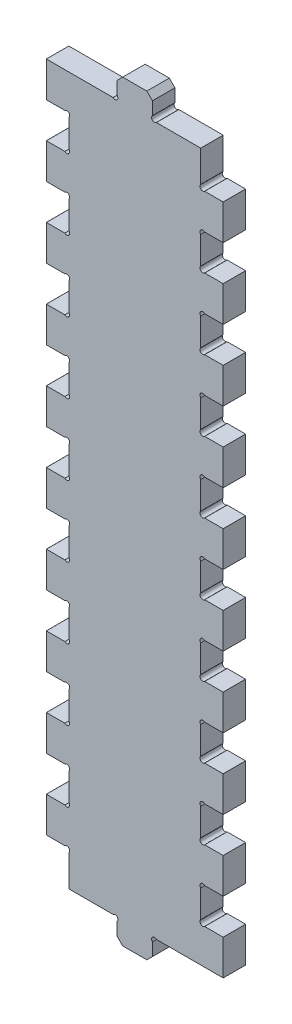
SolidWorks part; units mm, degrees
material "PVC Rigid"
ref_plane "Front Plane" through (0, 0, 0) normal (0, 0, 1) x (1, 0, 0)
ref_plane "Top Plane" through (0, 0, 0) normal (0, 1, 0) x (1, 0, 0)
ref_plane "Right Plane" through (0, 0, 0) normal (1, 0, 0) x (0, 0, -1)
sketch "Model" [suppressed]
  dimension "D3" = 0.7937
  dimension "D1" = 10
  dimension "D2" = 10
sketch "Sketch1" plane through (0, 0, 0) normal (0, 0, 1) x (1, 0, 0)
  line L1 (0, 0) -> (50, 0)
  line L2 (0, 0) -> (0, 200.0001)
  line L3 (0, 200.0001) -> (50, 200.0001)
  line L4 (50, 0) -> (50, 200.0001)
  dimension "D1" = 200.0001
  dimension "D2" = 50
extrude "Boss-Extrude1" add sketch "Sketch1" along normal blind 6.35
sketch "Sketch2" plane through (0, 0, 0) normal (0, 0, 1) x (1, 0, 0)
  line L0 (0, 100.0001) -> (50, 100.0001) construction
  line L1 (50, 200.0001) -> (0, 200.0001) construction
  line L2 (25, 200.0001) -> (25, 203.1751) construction
  line L3 (20, 206.3501) -> (30, 206.3501)
  line L4 (20, 206.3501) -> (20, 200.0001)
  line L5 (20, 200.0001) -> (30, 200.0001)
  line L6 (30, 206.3501) -> (30, 200.0001)
  line L7 (20, 206.3501) -> (30, 200.0001) construction
  line L8 (20, 200.0001) -> (30, 206.3501) construction
  line L9 (0, 200.0001) -> (0, 0) construction
  line L10 (50, 0) -> (50, 200.0001) construction
  line L11 (20, 0) -> (30, -6.35) construction
  line L12 (20, -6.35) -> (30, 0) construction
  line L13 (25, 0) -> (25, -3.175) construction
  line L14 (30, -6.35) -> (30, 0)
  line L15 (20, 0) -> (30, 0)
  line L16 (20, -6.35) -> (20, 0)
  line L17 (20, -6.35) -> (30, -6.35)
  dimension "D1" = 6.35
  dimension "D2" = 10
extrude "Boss-Extrude2" add sketch "Sketch2" along normal blind 6.35
sketch "Sketch3" plane through (0, 0, 6.35) normal (0, 0, 1) x (1, 0, 0)
  line L0 (25, 206.3501) -> (25, -6.35) construction
  line L1 (30, 206.3501) -> (20, 206.3501) construction
  line L2 (20, -6.35) -> (30, -6.35) construction
  line L3 (6.35, 200.0001) -> (6.35, 0) construction
  line L4 (20, 200.0001) -> (0, 200.0001) construction
  line L5 (0, 0) -> (20, 0) construction
  line L6 (0, 200.0001) -> (0, 0) construction
  line L7 (6.35, 0) -> (0, 0)
  line L8 (6.35, 0) -> (6.35, 10)
  line L9 (6.35, 10) -> (0, 10)
  line L10 (0, 0) -> (0, 10)
  line L11 (50, 0) -> (50, 10)
  line L12 (43.65, 10) -> (50, 10)
  line L13 (43.65, 0) -> (43.65, 10)
  line L14 (43.65, 0) -> (50, 0)
  dimension "D1" = 6.35
  dimension "D2" = 10
extrude "Cut-Extrude1" [suppressed] cut sketch "Sketch3" against normal blind 6.35
pattern_linear "LPattern2" [suppressed] count 10 spacing 20
sketch "Sketch4" [suppressed] plane through (0, 0, 6.35) normal (0, 0, 1) x (1, 0, 0)
  line L0 (0, 10) -> (6.35, 0) construction
  line L1 (6.35, 10) -> (5.2275, 10) construction
  line L2 (0.5613, 0.5613) -> (5.7887, 0.5613) construction
  line L3 (0.5613, 0.5613) -> (0.5613, 9.4387) construction
  line L4 (0.5613, 9.4387) -> (5.7887, 9.4387) construction
  line L5 (5.7887, 0.5613) -> (5.7887, 9.4387) construction
  line L6 (0.5613, 0.5613) -> (5.7887, 9.4387) construction
  line L7 (0.5613, 9.4387) -> (5.7887, 0.5613) construction
  line L8 (6.35, 10) -> (0, 10) construction
  line L9 (6.35, 10) -> (6.35, 8.8775) construction
  line L10 (6.35, 0) -> (6.35, 10) construction
  line L11 (25, 206.3501) -> (25, -6.35) construction
  line L12 (30, 206.3501) -> (20, 206.3501) construction
  line L13 (20, -6.35) -> (30, -6.35) construction
  line L14 (44.2113, 9.4387) -> (44.2113, 20.5613) construction
  line L15 (43.65, 10) -> (43.65, 8.8775) construction
  line L16 (49.4387, 9.4387) -> (44.2113, 0.5613) construction
  line L17 (49.4387, 0.5613) -> (44.2113, 9.4387) construction
  line L18 (44.2113, 0.5613) -> (44.2113, 9.4387) construction
  line L19 (49.4387, 9.4387) -> (44.2113, 9.4387) construction
  line L20 (49.4387, 0.5613) -> (49.4387, 9.4387) construction
  line L21 (49.4387, 0.5613) -> (44.2113, 0.5613) construction
  line L22 (43.65, 10) -> (44.7725, 10) construction
  line L23 (5.7887, 9.4387) -> (5.7887, 20.5613) construction
  line L24 (50, 10) -> (43.65, 0) construction
  circle A0 centre (5.7887, 9.4387) radius 0.7938
  circle A4 centre (5.7887, 20.5613) radius 0.7938
  circle A7 centre (44.2113, 20.5613) radius 0.7937
  circle A8 centre (44.2113, 9.4387) radius 0.7937
  point P4 (3.175, 5)
  point P40 (46.825, 5)
  dimension "D1" = 1.5875
extrude "Cut-Extrude3" [suppressed] cut sketch "Sketch4" against normal blind 6.35
pattern_linear "LPattern3" [suppressed] count 9 spacing 20
sketch "Sketch8" plane through (0, 0, 6.35) normal (0, 0, 1) x (1, 0, 0)
  line L0 (6.35, 200.0001) -> (6.35, 0) construction
  line L1 (20, 200.0001) -> (0, 200.0001) construction
  line L2 (0, 0) -> (20, 0) construction
  line L3 (0, 200.0001) -> (0, 0) construction
  line L4 (43.65, 200.0001) -> (43.65, 0) construction
  line L5 (0, 0) -> (6.35, 0)
  line L6 (0, 0) -> (0, 10)
  line L7 (0, 10) -> (6.35, 10)
  line L8 (6.35, 0) -> (6.35, 10)
  line L9 (50, 200.0001) -> (30, 200.0001) construction
  line L10 (30, 0) -> (50, 0) construction
  line L11 (50, 0) -> (50, 200.0001) construction
  line L12 (43.65, 10) -> (50, 10)
  line L13 (43.65, 10) -> (43.65, 20)
  line L14 (43.65, 20) -> (50, 20)
  line L15 (50, 10) -> (50, 20)
  dimension "D1" = 6.35
  dimension "D2" = 10
  dimension "D3" = 10
  dimension "D4" = 6.35
  dimension "D5" = 10
extrude "Cut-Extrude6" cut sketch "Sketch8" against normal through all
pattern_linear "LPattern4" count 10 spacing 20 along (0, 1, 0) of "Cut-Extrude6"
sketch "Sketch9" plane through (0, 0, 6.35) normal (0, 0, 1) x (1, 0, 0)
  line L0 (0, 30) -> (6.35, 20) construction
  line L1 (6.35, 30) -> (5.2275, 30) construction
  line L2 (0.5613, 20.5613) -> (5.7887, 20.5613) construction
  line L3 (0.5613, 20.5613) -> (0.5613, 29.4388) construction
  line L4 (0.5613, 29.4388) -> (5.7887, 29.4388) construction
  line L5 (5.7887, 20.5613) -> (5.7887, 29.4388) construction
  line L6 (0.5613, 20.5613) -> (5.7887, 29.4388) construction
  line L7 (0.5613, 29.4388) -> (5.7887, 20.5613) construction
  line L8 (6.35, 30) -> (0, 30) construction
  line L9 (6.35, 30) -> (6.35, 28.8775) construction
  line L10 (6.35, 20) -> (6.35, 30) construction
  line L11 (43.65, 20) -> (50, 10) construction
  line L12 (43.65, 20) -> (44.7725, 20) construction
  line L13 (44.2113, 10.5613) -> (49.4387, 10.5613) construction
  line L14 (44.2113, 10.5613) -> (44.2113, 19.4387) construction
  line L15 (44.2113, 19.4387) -> (49.4387, 19.4387) construction
  line L16 (49.4387, 10.5613) -> (49.4387, 19.4387) construction
  line L17 (44.2113, 10.5613) -> (49.4387, 19.4387) construction
  line L18 (44.2113, 19.4387) -> (49.4387, 10.5613) construction
  line L19 (50, 20) -> (43.65, 20) construction
  line L20 (43.65, 20) -> (43.65, 18.8775) construction
  line L21 (43.65, 20) -> (43.65, 10) construction
  line L22 (50, 20) -> (50, 30) construction
  circle A0 centre (5.7887, 29.4388) radius 0.7938
  circle A1 centre (5.7887, 20.5613) radius 0.7938
  circle A2 centre (44.2113, 19.4387) radius 0.7937
  circle A3 centre (44.2113, 10.5613) radius 0.7937
  point P4 (3.175, 25)
  point P23 (46.825, 15)
  dimension "D1" = 1.5875
  dimension "D2" = 10
extrude "Cut-Extrude7" cut sketch "Sketch9" against normal through all
pattern_linear "LPattern5" count 9 spacing 20 along (0, 1, 0) of "Cut-Extrude7"
sketch "Sketch10" plane through (0, 0, 6.35) normal (0, 0, 1) x (1, 0, 0)
  line L0 (0, 10) -> (6.35, 0) construction
  line L1 (5.2275, 10) -> (6.35, 10) construction
  line L2 (0.5613, 0.5613) -> (5.7887, 0.5613) construction
  line L3 (0.5613, 0.5613) -> (0.5613, 9.4387) construction
  line L4 (0.5613, 9.4387) -> (5.7887, 9.4387) construction
  line L5 (5.7887, 0.5613) -> (5.7887, 9.4387) construction
  line L6 (0.5613, 0.5613) -> (5.7887, 9.4387) construction
  line L7 (0.5613, 9.4387) -> (5.7887, 0.5613) construction
  line L8 (6.35, 10) -> (0, 10) construction
  line L9 (6.35, 10) -> (6.35, 8.8775) construction
  line L10 (6.35, 0) -> (6.35, 10) construction
  line L11 (6.35, 5) -> (3.175, 5) construction
  line L12 (0, 200.0001) -> (50, 0) construction
  line L13 (43.65, 200.0001) -> (50, 190.0001) construction
  line L14 (44.7725, 190.0001) -> (43.65, 190.0001) construction
  line L15 (44.2113, 190.5614) -> (49.4387, 190.5614) construction
  line L16 (44.2113, 190.5614) -> (44.2113, 199.4388) construction
  line L17 (44.2113, 199.4388) -> (49.4387, 199.4388) construction
  line L18 (49.4387, 190.5614) -> (49.4387, 199.4388) construction
  line L19 (44.2113, 190.5614) -> (49.4387, 199.4388) construction
  line L20 (44.2113, 199.4388) -> (49.4387, 190.5614) construction
  line L21 (43.65, 190.0001) -> (50, 190.0001) construction
  line L22 (43.65, 190.0001) -> (43.65, 191.1226) construction
  line L23 (43.65, 200.0001) -> (43.65, 190.0001) construction
  circle A0 centre (5.7887, 9.4387) radius 0.7938
  circle A2 centre (44.2113, 190.5614) radius 0.7937
  point P4 (3.175, 5)
  point P28 (46.825, 195.0001)
  dimension "D1" = 1.5875
  dimension "D2" = 1.5875
extrude "Cut-Extrude8" cut sketch "Sketch10" against normal through all
chamfer "Chamfer1" distance 1.5875 angle 45 4 edges at (30, -6.35, 3.175) (20, -6.35, 3.175) (20, 206.3501, 3.175) (30, 206.3501, 3.175)
sketch "Sketch5" [suppressed] plane through (0, 0, 6.35) normal (0, 0, 1) x (1, 0, 0)
  line L0 (6.35, 180.0001) -> (0, 190.0001) construction
  line L1 (6.35, 190.0001) -> (5.2275, 190.0001) construction
  line L2 (0.5613, 180.5614) -> (5.7887, 180.5614) construction
  line L3 (0.5613, 180.5614) -> (0.5613, 189.4388) construction
  line L4 (0.5613, 189.4388) -> (5.7887, 189.4388) construction
  line L5 (5.7887, 180.5614) -> (5.7887, 189.4388) construction
  line L6 (0.5613, 180.5614) -> (5.7887, 189.4388) construction
  line L7 (0.5613, 189.4388) -> (5.7887, 180.5614) construction
  line L8 (6.35, 190.0001) -> (0, 190.0001) construction
  line L9 (6.35, 190.0001) -> (6.35, 188.8776) construction
  line L10 (6.35, 181.1226) -> (6.35, 190.0001) construction
  line L15 (25, 206.3501) -> (25, -6.35) construction
  line L16 (28.4125, 206.3501) -> (21.5875, 206.3501) construction
  line L17 (21.5875, -6.35) -> (28.4125, -6.35) construction
  line L20 (43.65, 190.0001) -> (43.65, 188.8776) construction
  line L21 (49.4387, 189.4388) -> (44.2113, 180.5614) construction
  line L22 (49.4387, 180.5614) -> (44.2113, 189.4388) construction
  line L23 (44.2113, 180.5614) -> (44.2113, 189.4388) construction
  line L24 (49.4387, 189.4388) -> (44.2113, 189.4388) construction
  line L25 (49.4387, 180.5614) -> (49.4387, 189.4388) construction
  line L26 (49.4387, 180.5614) -> (44.2113, 180.5614) construction
  line L27 (43.65, 190.0001) -> (44.7725, 190.0001) construction
  line L28 (43.65, 180.0001) -> (50, 190.0001) construction
  line L29 (50, 100.0001) -> (0, 100.0001) construction
  arc A0 (5.2275, 180.0001) -> (6.35, 181.1226) centre (5.7887, 180.5614) ccw construction
  circle A1 centre (5.7887, 189.4388) radius 0.7938
  circle A4 centre (44.2113, 189.4388) radius 0.7937
  point P6 (3.175, 185.0001)
  point P51 (46.825, 185.0001)
  point P56 (25, 100.0001)
  dimension "D1" = 1.5875
extrude "Cut-Extrude4" [suppressed] cut sketch "Sketch5" against normal blind 6.35
sketch "Sketch11" plane through (0, 0, 0) normal (0, 0, 1) x (1, 0, 0)
  line L0 (28.4125, 206.3501) -> (21.5875, 206.3501) construction
  line L11 (20, 201.1226) -> (20, 200.0001) construction
  line L13 (20, 200.0001) -> (18.8775, 200.0001) construction
  line L15 (25, 206.3501) -> (25, -6.35) construction
  line L18 (30, 200.0001) -> (31.1225, 200.0001) construction
  line L19 (30, 201.1226) -> (30, 200.0001) construction
  line L29 (50, 100.0001) -> (0, 100.0001) construction
  circle A2 centre (19.4387, 200.5614) radius 0.7937
  circle A3 centre (30.5613, 200.5614) radius 0.7937
  circle A5 centre (19.4387, -0.5613) radius 0.7937
  circle A6 centre (30.5613, -0.5613) radius 0.7937
  point P56 (25, 100.0001)
  dimension "D1" = 1.5875
  dimension "D2" = 19.4387
  dimension "D3" = 100.0001
  dimension "D4" = 200.0001
extrude "Cut-Extrude10" cut sketch "Sketch11" along normal through all
sketch "Sketch6" [suppressed] plane through (0, 0, 6.35) normal (0, 0, 1) x (1, 0, 0)
  line L0 (6.604, 2.032) -> (43.65, 2.032) construction
  line L1 (43.65, 8.8775) -> (43.65, 0) construction
  line L2 (6.35, 0) -> (18.8775, 0) construction
  line L4 (0, 20) -> (0, 10) construction
  text T0 "CSR" font "Consolas" height 3.5
  dimension "D1" = 2.032
  dimension "D2" = 6.604
extrude "Cut-Extrude5" [suppressed] cut sketch "Sketch6" against normal blind 2.54
sketch "Sketch12" plane through (0, 0, 6.35) normal (0, 0, 1) x (1, 0, 0)
  line L0 (6.604, 2.032) -> (40.0372, 2.032) construction
  text T0 "CSL" font "Consolas" height 3.5
  dimension "D1" = 2.032
  dimension "D2" = 6.604
extrude "Cut-Extrude11" [suppressed] cut sketch "Sketch12" against normal blind 2.54
sketch "Sketch13" [suppressed] plane through (0, 0, 6.35) normal (0, 0, 1) x (1, 0, 0)
  line L0 (0, 10) -> (6.35, 0) construction
  line L1 (5.2275, 10) -> (0, 10) construction
  line L2 (6.337, -0.0127) -> (0.013, -0.0127)
  line L3 (6.337, -0.0127) -> (6.337, 10.0127)
  line L4 (6.337, 10.0127) -> (0.013, 10.0127)
  line L5 (0.013, -0.0127) -> (0.013, 10.0127)
  line L6 (6.337, -0.0127) -> (0.013, 10.0127) construction
  line L7 (6.337, 10.0127) -> (0.013, -0.0127) construction
  line L8 (25, 206.3501) -> (25, -6.35) construction
  line L9 (28.4125, 206.3501) -> (21.5875, 206.3501) construction
  line L10 (21.5875, -6.35) -> (28.4125, -6.35) construction
  line L11 (43.663, 10.0127) -> (49.987, -0.0127) construction
  line L12 (43.663, -0.0127) -> (49.987, 10.0127) construction
  line L13 (50, 10) -> (43.65, 0) construction
  line L14 (49.987, -0.0127) -> (49.987, 10.0127)
  line L15 (43.663, 10.0127) -> (49.987, 10.0127)
  line L16 (43.663, -0.0127) -> (43.663, 10.0127)
  line L17 (43.663, -0.0127) -> (49.987, -0.0127)
  arc A0 (6.35, 8.8775) -> (5.2275, 10) centre (5.7887, 9.4387) ccw construction
  point P4 (3.175, 5)
  point P26 (46.825, 5)
  dimension "D1" = 0.0127
extrude "Cut-Extrude12" [suppressed] cut sketch "Sketch13" against normal through all
pattern_linear "LPattern6" [suppressed] count 10 spacing 20
sketch "Sketch14" plane through (0, 0, 6.35) normal (0, 0, 1) x (1, 0, 0)
  line L0 (0, 10) -> (6.35, 0) construction
  line L1 (5.2275, 10) -> (0, 10) construction
  line L2 (0.013, -0.0127) -> (6.337, -0.0127)
  line L3 (0.013, -0.0127) -> (0.013, 10.0127)
  line L4 (0.013, 10.0127) -> (6.337, 10.0127)
  line L5 (6.337, -0.0127) -> (6.337, 10.0127)
  line L6 (0.013, -0.0127) -> (6.337, 10.0127) construction
  line L7 (0.013, 10.0127) -> (6.337, -0.0127) construction
  line L8 (43.65, 20) -> (50, 10) construction
  line L9 (50, 20) -> (44.7725, 20) construction
  line L10 (43.663, 9.9873) -> (49.987, 9.9873)
  line L11 (43.663, 9.9873) -> (43.663, 20.0127)
  line L12 (43.663, 20.0127) -> (49.987, 20.0127)
  line L13 (49.987, 9.9873) -> (49.987, 20.0127)
  line L14 (43.663, 9.9873) -> (49.987, 20.0127) construction
  line L15 (43.663, 20.0127) -> (49.987, 9.9873) construction
  arc A0 (6.35, 8.8775) -> (5.2275, 10) centre (5.7887, 9.4387) ccw construction
  arc A1 (44.7725, 20) -> (43.65, 18.8775) centre (44.2113, 19.4387) ccw construction
  point P4 (3.175, 5)
  point P9 (46.825, 15)
  dimension "D1" = 0.0127
  dimension "D2" = 0.0127
extrude "Cut-Extrude13" cut sketch "Sketch14" against normal through all
pattern_linear "LPattern7" count 10 spacing 20 along (0, 1, 0) of "Cut-Extrude13"
sketch "Sketch15" plane through (0, 0, 6.35) normal (0, 0, 1) x (1, 0, 0)
  line L1 (0, 200.0001) -> (2.032, 200.0001) construction
  line L2 (0, 200.0001) -> (0, 197.9681) construction
  line L3 (0, 197.9681) -> (2.032, 197.9681) construction
  line L4 (2.032, 200.0001) -> (2.032, 197.9681) construction
  circle A0 centre (2.032, 197.9681) radius 0.7938
  dimension "D2" = 1.5875
  dimension "D1" = 2.032
extrude "Cut-Extrude14" [suppressed] cut sketch "Sketch15" against normal blind 3.175
pattern_linear "LPattern8" [suppressed] count 3 spacing 2.032
equation "\"tHeight\"=0.25"
equation "\"D1@Sketch2\"=\"tHeight\""
equation "\"tWidth\"=0.393701"
equation "\"D2@Sketch2\"=\"tWidth\""
equation "\"D1@Sketch1\"=\"tWidth\"*20"
equation "\"D1@Sketch3\"=\"tHeight\""
equation "\"D2@Sketch3\"=\"tWidth\""
equation "\"D3@LPattern2\"=\"tWidth\"*2"
equation "\"D3@LPattern3\"=\"tWidth\"*2"
equation "\"D1@Sketch8\"=\"tHeight\""
equation "\"D2@Sketch8\"=\"tWidth\""
equation "\"D3@Sketch8\"=\"tWidth\""
equation "\"D4@Sketch8\"=\"tHeight\""
equation "\"D5@Sketch8\"=\"tWidth\""
equation "\"D3@LPattern4\"=\"tWidth\"*2"
equation "\"D3@LPattern5\"=\"tWidth\"*2"
equation "\"D2@Sketch9\"=\"tWidth\""
equation "\"tol\"=0.0005"
equation "\"D1@Sketch13\"=\"tol\""
equation "\"D3@LPattern6\"=\"tWidth\"*2"
equation "\"D1@Sketch14\"=\"tol\""
equation "\"D2@Sketch14\"=\"tol\""
equation "\"version\"= 3"
equation "\"D1@LPattern8\"=\"version\""
